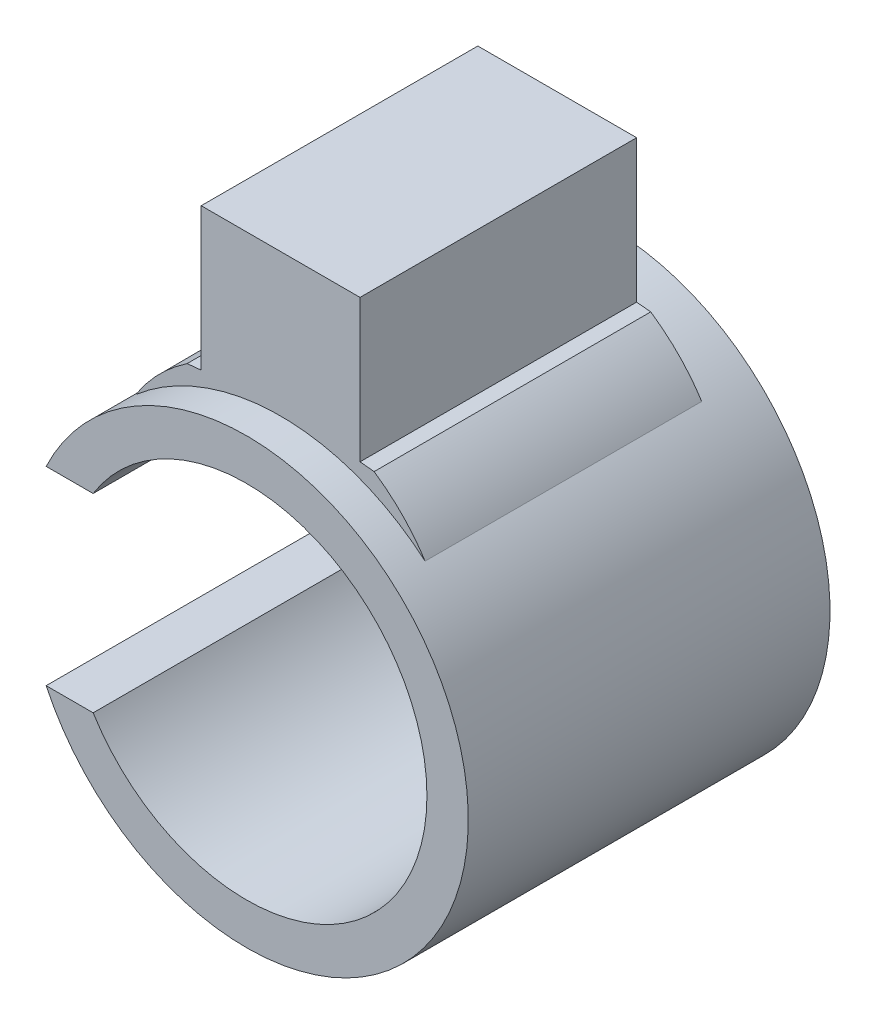
SolidWorks part; units mm, degrees
ref_plane "Front Plane" through (0, 0, 0) normal (0, 0, 1) x (1, 0, 0)
ref_plane "Top Plane" through (0, 0, 0) normal (0, 1, 0) x (1, 0, 0)
ref_plane "Right Plane" through (0, 0, 0) normal (1, 0, 0) x (0, 0, -1)
sketch "Sketch1" plane through (0, 0, 0) normal (1, 0, 0) x (0, 0, -1)
  line L0 (53, 0) -> (88.6301, 0) construction
  line L6 (18, 19) -> (53, 19)
  line L7 (53, 19) -> (53, 0)
  line L9 (18, 19) -> (18, 23.3557)
  line L14 (18, 23.3557) -> (56.0968, 23.3557)
  line L15 (56.0968, 23.3557) -> (56.0968, 0)
  line L16 (56.0968, 0) -> (53, 0)
  dimension "D1" = 19
  dimension "D2" = 35
revolve "Revolve1" add sketch "Sketch1" angle 360 about L0
sketch "Sketch2" plane through (0, 0, -56.0968) normal (0, 0, -1) x (-1, 0, 0)
  circle A0 centre (0, 0) radius 7.6921
extrude "Cut-Extrude1" cut sketch "Sketch2" against normal blind 10
sketch "Sketch3" plane through (0, 0, 0) normal (0, 0, 1) x (1, 0, 0)
  line L0 (0, 0) -> (0, 23.3557)
  circle A0 centre (0, 0) radius 23.3557 construction
  point P6 (0, 0)
ref_plane "Plane1" through (0, 23.3557, 0) normal (0, 1, 0) x (1, 0, 0)
sketch "Sketch4" plane through (0, 23.3557, 0) normal (0, 1, 0) x (1, 0, 0)
  line L1 (8.3629, 50.7214) -> (-8.3629, 50.7214)
  line L2 (8.3629, 50.7214) -> (8.3629, 21.5888)
  line L3 (8.3629, 21.5888) -> (-8.3629, 21.5888)
  line L4 (-8.3629, 50.7214) -> (-8.3629, 21.5888)
  line L5 (8.3629, 50.7214) -> (-8.3629, 21.5888) construction
  line L6 (8.3629, 21.5888) -> (-8.3629, 50.7214) construction
  point P0 (0, 36.1551)
extrude "Boss-Extrude1" add sketch "Sketch4" along normal blind 15 separate body
sketch "Sketch5" plane through (0, 0, -50.7214) normal (0, 0, -1) x (-1, 0, 0)
  line L0 (9.8507, 23.2113) -> (8.3629, 23.3557)
  line L1 (0, 23.3557) -> (7.5466, 24.3869)
  line L2 (7.5466, 24.3869) -> (8.3629, 23.3557)
  line L3 (0, 30.8532) -> (0, -30.8532) construction
  line L4 (0, 23.3557) -> (-7.5466, 24.3869)
  line L5 (-7.5466, 24.3869) -> (-8.3629, 23.3557)
  line L6 (-9.8507, 23.2113) -> (-8.3629, 23.3557)
  arc A2 (15.2158, 17.7192) -> (-15.2158, 17.7192) centre (0, 0) ccw
  spline S0 degree 2 poles (9.8507, 23.2113) (13.1769, 20.9459) (15.2158, 17.7192) knots 0 0 0 0.793491 0.793491 0.793491
  spline S1 degree 2 poles (-9.8507, 23.2113) (-13.1769, 20.9459) (-15.2158, 17.7192) knots 0 0 0 0.793491 0.793491 0.793491
  line M12 (-8.3629, 23.3557) -> (8.3629, 23.3557)
extrude "Boss-Extrude2" add sketch "Sketch5" against normal up to surface (29.1326 mm away) contours L6 S1 A2 M12 | S0 L0 A2 M12 up to face at (0, 30.8557, -21.5888)
sketch "Sketch6" plane through (0, 0, 0) normal (0, 0, 1) x (1, 0, 0)
  line L0 (-16.1555, -10) -> (-21.1066, -10)
  line L9 (-16.1555, 10) -> (-21.1066, 10)
  arc A4 (-16.1555, 10) -> (-16.1555, -10) centre (0, 0) ccw
  arc A5 (-21.1066, 10) -> (-21.1066, -10) centre (0, 0) ccw
  point P0 (0, 0)
extrude "Cut-Extrude2" cut sketch "Sketch6" against normal through all
